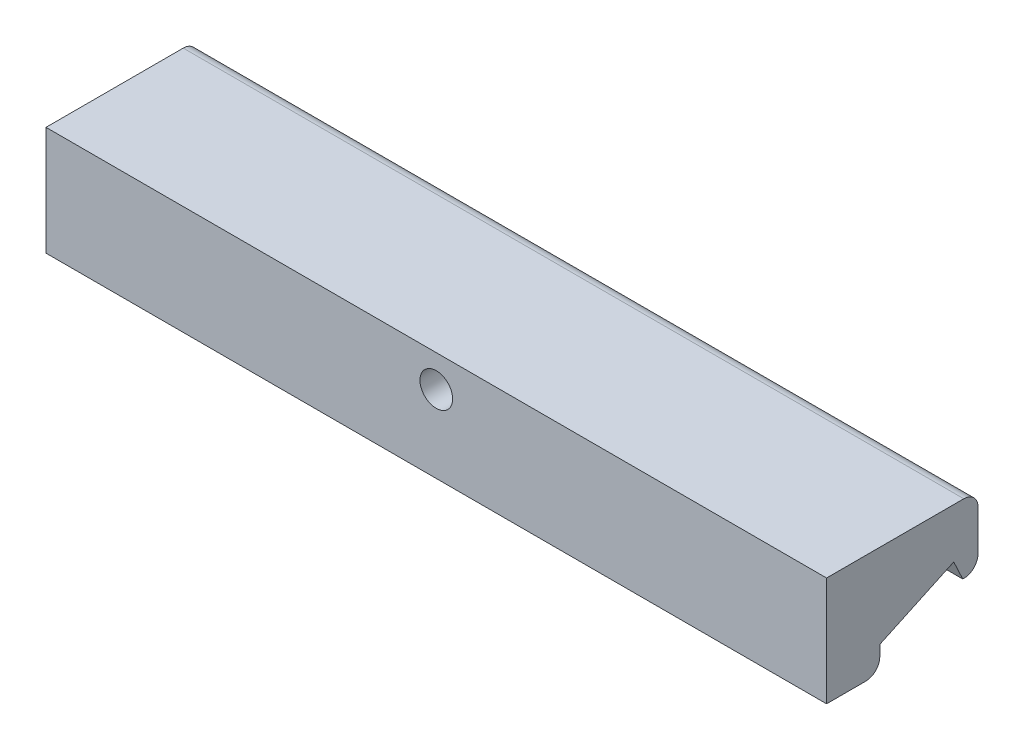
SolidWorks part; units mm, degrees
ref_plane "Front Plane" through (0, 0, 0) normal (0, 0, 1) x (1, 0, 0)
ref_plane "Top Plane" through (0, 0, 0) normal (0, 1, 0) x (1, 0, 0)
ref_plane "Right Plane" through (0, 0, 0) normal (1, 0, 0) x (0, 0, -1)
sketch "Sketch1" plane through (0, 0, 0) normal (1, 0, 0) x (0, 0, -1)
  line L0 (0, 0) -> (5.4995, 0)
  line L2 (21.3407, 7.6355) -> (21.3407, 13.3601)
  line L3 (19.3407, 15.3601) -> (0, 15.3601)
  line L4 (0, 15.3601) -> (0, 0)
  line L6 (19.1904, 5.6412) -> (17.9225, 8.3601)
  line L7 (17.9225, 8.3601) -> (7.5, 3.5)
  line L8 (7.5, 3.5) -> (7.5, 2.0005)
  arc A0 (19.3407, 15.3601) -> (21.3407, 13.3601) centre (19.3407, 13.3601) cw
  arc A1 (19.1904, 5.6412) -> (21.3407, 7.6355) centre (19.3407, 7.6355) ccw
  arc A2 (5.4995, 0) -> (7.5, 2.0005) centre (5.4995, 2.0005) ccw
  dimension "D7" = 4
  dimension "D4" = 4
  dimension "D8" = 4.0011
  dimension "D3" = 11.5
  dimension "D1" = 7.5
  dimension "D5" = 7
  dimension "D6" = 3
extrude "ProfileBoss-Extrude1" add sketch "Sketch1" along normal blind 110
sketch "Sketch3" plane through (0, 0, 0) normal (0, 0, 1) x (1, 0, 0)
  line L0 (0, 15.3601) -> (0, 0) construction
  circle A0 centre (55, 10.8601) radius 2.3
  dimension "D1" = 4.6
  dimension "D4" = 4.5
  dimension "D2" = 55
extrude "MountingHolesCut-Extrude3" cut sketch "Sketch3" against normal blind 4.5
equation "\"LightStripShortLength\"= 80mm"
equation "\"D1@ProfileBoss-Extrude1\" = \"LightStripMidLength\""
equation "\"LightStripWidth\"= 11.5mm'Spec"
equation "\"D3@Sketch1\"=\"LightStripWidth\""
equation "\"LightStripGuideMountingHoleFromMiddle\"= \"LightStripMidLength\" / 2"
equation "\"D2@Sketch3\"=\"LightStripGuideMountingHoleFromMiddle\""
equation "\"LedStripLength\"= 270mm'Spec"
equation "\"LightStripMidLength\"= \"LedStripLength\" - \"LightStripShortLength\" * 2"
equation "\"LightStripGuideMountingHoleFromTop\"= 4.5mm"
equation "\"D4@Sketch3\"=\"LightStripGuideMountingHoleFromTop\""
